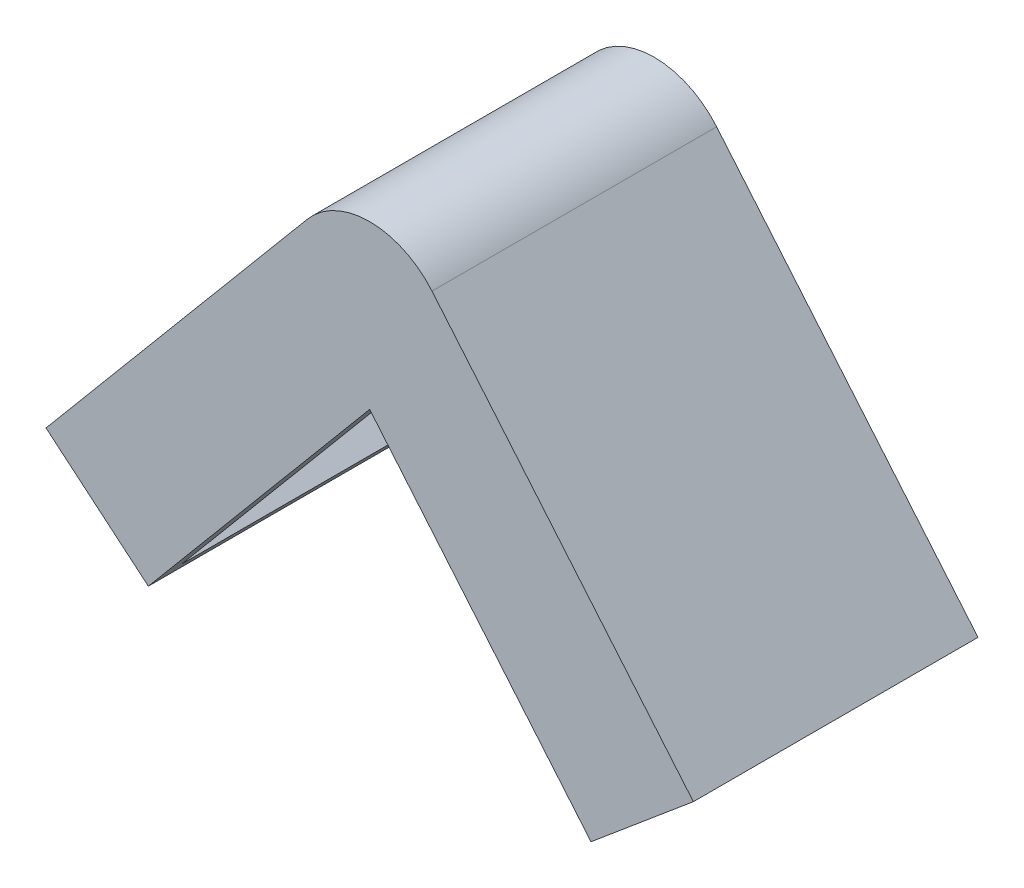
SolidWorks part; units mm, degrees
ref_plane "Front Plane" through (0, 0, 0) normal (0, 0, 1) x (1, 0, 0)
ref_plane "Top Plane" through (0, 0, 0) normal (0, 1, 0) x (1, 0, 0)
ref_plane "Right Plane" through (0, 0, 0) normal (1, 0, 0) x (0, 0, -1)
sketch "Sketch1" plane through (0, 0, 0) normal (0, 0, 1) x (1, 0, 0)
  line L0 (0, -25.4) -> (-69.127, -107.7823)
  line L1 (-19.4575, 16.3268) -> (-101.0916, -80.9608)
  line L2 (0, -25.4) -> (69.127, -107.7823)
  line L3 (19.4575, 16.3268) -> (101.0916, -80.9608)
  line L4 (0, -25.4) -> (25.4, -25.4) construction
  line L5 (25.4, -25.4) -> (-29.9572, -25.4) construction
  line L6 (-101.0916, -80.9608) -> (-69.127, -107.7823)
  line L7 (69.127, -107.7823) -> (101.0916, -80.9608)
  line L8 (-19.4575, 16.3268) -> (12.5071, -10.4947)
  line L9 (12.5071, -10.4947) -> (0, -25.4)
  line L10 (0, -25.4) -> (-12.5071, -10.4947)
  line L11 (-12.5071, -10.4947) -> (19.4575, 16.3268)
  circle A0 centre (0, 0) radius 25.4
  point P13 (6.2535, -17.9473)
  dimension "D1" = 50.8
  dimension "D2" = 80
  dimension "D3" = 50
  dimension "D4" = 127
extrude "Boss-Extrude1" add sketch "Sketch1" along normal blind 88.9 contours A0 L2 L7 L3 | L11 A0 L8 | L9 A0 L11 L8 | L11 L10 L9 L8 | L8 A0 L10 L11 | A0 L1 L6 L0
sketch "Sketch3" plane through (12.5071, -10.4947, 0) normal (0.766, -0.6428, 0) x (0, 0, -1)
  line L8 (-82.55, -25.8075) -> (-6.35, -25.8075)
  line L9 (-6.35, -25.8075) -> (-6.35, -120.65)
  line L10 (-6.35, -120.65) -> (-82.55, -120.65)
  line L11 (-82.55, -120.65) -> (-82.55, -25.8075)
extrude "Cut-Extrude1" cut sketch "Sketch3" along normal blind 3.048 and the other way blind 36.576
sketch "Sketch5" plane through (0, 0, 0) normal (0, 0, -1) x (-1, 0, 0)
  line L0 (-19.4575, 16.3268) -> (0, -25.4)
  line L1 (0, -25.4) -> (19.4575, 16.3268)
sketch "Sketch6" plane through (0, 0, 88.9) normal (0, 0, 1) x (1, 0, 0)
  line L0 (-19.4575, 16.3268) -> (0, -25.4)
